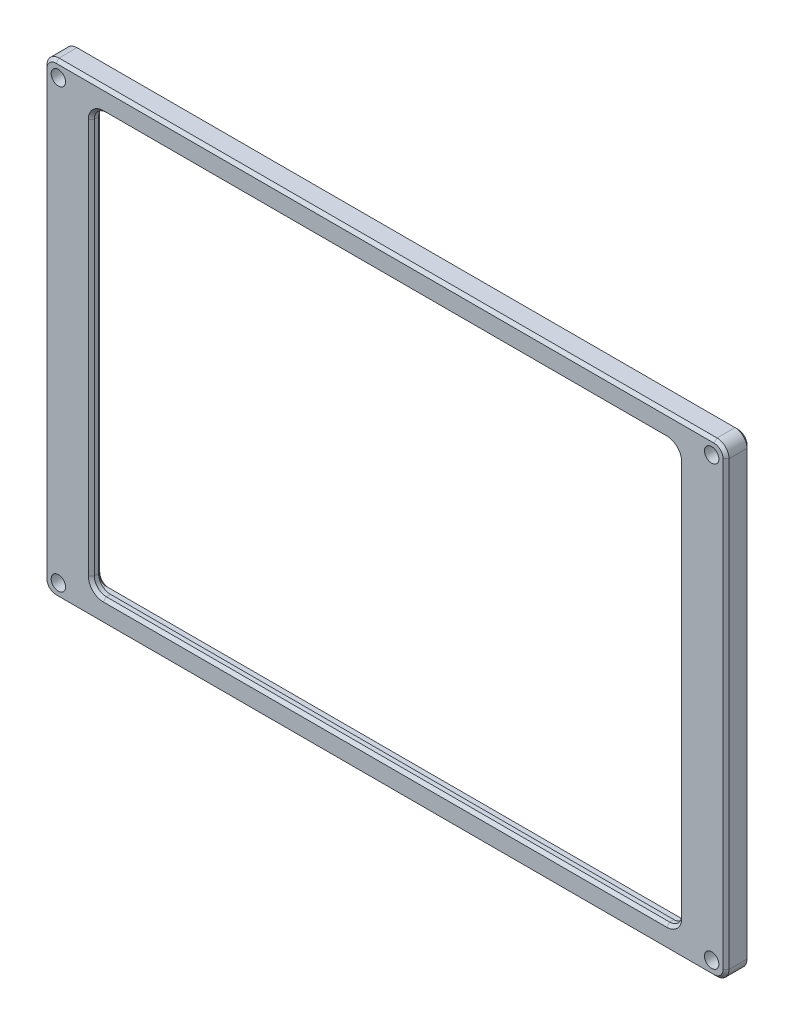
SolidWorks part; units mm, degrees
ref_plane "Front Plane" through (0, 0, 0) normal (0, 0, 1) x (1, 0, 0)
ref_plane "Top Plane" through (0, 0, 0) normal (0, 1, 0) x (1, 0, 0)
ref_plane "Right Plane" through (0, 0, 0) normal (1, 0, 0) x (0, 0, -1)
sketch "Sketch1" plane through (0, 0, 0) normal (0, 0, 1) x (1, 0, 0)
  line L1 (-56.9, -38.9) -> (56.9, -38.9)
  line L2 (-56.9, -38.9) -> (-56.9, 38.9)
  line L3 (-56.9, 38.9) -> (56.9, 38.9)
  line L4 (56.9, -38.9) -> (56.9, 38.9)
  line L5 (-56.9, -38.9) -> (56.9, 38.9) construction
  line L6 (-56.9, 38.9) -> (56.9, -38.9) construction
  line L7 (-49, -35) -> (49, -35)
  line L8 (-49, -35) -> (-49, 35)
  line L9 (-49, 35) -> (49, 35)
  line L10 (49, -35) -> (49, 35)
  line L11 (-49, -35) -> (49, 35) construction
  line L12 (-49, 35) -> (49, -35) construction
  point P0 (0, 0)
  point P5 (0, 0)
  dimension "D1" = 113.8
  dimension "D2" = 77.8
  dimension "D3" = 70
  dimension "D4" = 98
extrude "Boss-Extrude1" add sketch "Sketch1" along normal blind 4
hole_wizard "M2 Clearance Hole1" positions "Sketch2" profile "Sketch3" hole size "M2" standard "ANSI Metric" end condition up to next
sketch "Sketch2" plane through (0, 0, 4) normal (0, 0, 1) x (1, 0, 0)
  line L1 (-54.5, -36.5) -> (54.5, -36.5)
  line L2 (-54.5, -36.5) -> (-54.5, 36.5)
  line L3 (-54.5, 36.5) -> (54.5, 36.5)
  line L4 (54.5, -36.5) -> (54.5, 36.5)
  line L5 (-54.5, -36.5) -> (54.5, 36.5) construction
  line L6 (-54.5, 36.5) -> (54.5, -36.5) construction
  point P1 (0, 0)
  point P2 (54.5, 36.5)
  point P5 (-54.5, -36.5)
  point P6 (-54.5, 36.5)
  point P7 (54.5, -36.5)
  dimension "D1" = 109
  dimension "D2" = 73
sketch "Sketch3" plane through (0, 0, 4) normal (1, 0, 0) x (0, -1, 0)
  line L0 (0, 0) -> (0, 4)
  line L1 (0, 4) -> (1.2, 4)
  line L2 (1.2, 4) -> (1.2, 0)
  line L5 (1.2, 0) -> (0, 0)
  line L11 (0, -6.35) -> (0, 107.95) construction
  dimension "Thru Hole Dia." = 2.4
  dimension "Thru Hole Depth" = 4
fillet "Fillet1" radius 2 4 edges at (56.9, -38.9, 2) (-56.9, -38.9, 2) (56.9, 38.9, 2) (-56.9, 38.9, 2)
fillet "Fillet2" radius 2 4 edges at (49, 35, 2) (-49, -35, 2) (49, -35, 2) (-49, 35, 2)
sketch "Sketch5" plane through (0, 0, 0) normal (0, 0, -1) x (-1, 0, 0)
  line L1 (-51.1, -36.5) -> (51.1, -36.5)
  line L2 (-51.1, -36.5) -> (-51.1, 36.5)
  line L3 (-51.1, 36.5) -> (51.1, 36.5)
  line L4 (51.1, -36.5) -> (51.1, 36.5)
  line L5 (-51.1, -36.5) -> (51.1, 36.5) construction
  line L6 (-51.1, 36.5) -> (51.1, -36.5) construction
  line L16 (-54.9, 38.9) -> (54.9, 38.9) construction
  point P0 (0, 0)
  point P5 (0, 0)
  dimension "D1" = 73
  dimension "D2" = 102.2
  dimension "D4" = 2.4
extrude "Cut-Extrude2" cut sketch "Sketch5" against normal offset from surface (2.8 mm away) 1.2 up to face at (55.7, 36.5, 4)
fillet "Fillet5" radius 1 4 edges at (51.1, -36.5, 1.4) (-51.1, 36.5, 1.4) (-51.1, -36.5, 1.4) (51.1, 36.5, 1.4)
chamfer "Chamfer1" distance 0.5 angle 45 32 edges at (-49, 0, 4) (-48.4142, -34.4142, 4) (-48.4142, 34.4142, 4) (0, -35, 4) (0, 35, 4) (48.4142, -34.4142, 4) (48.4142, 34.4142, 4) (49, 0, 4) (-51.1, 0, 0) (-50.8071, 36.2071, 0) (-50.8071, -36.2071, 0) (0, 36.5, 0) (0, -36.5, 0) (50.8071, 36.2071, 0) (50.8071, -36.2071, 0) (51.1, 0, 0) (0, 38.9, 4) (-56.3142, 38.3142, 4) (56.3142, 38.3142, 4) (-56.9, 0, 4) (56.9, 0, 4) (-56.3142, -38.3142, 4) (56.3142, -38.3142, 4) (0, -38.9, 4) (-56.9, 0, 0) (-56.3142, -38.3142, 0) (-56.3142, 38.3142, 0) (0, -38.9, 0) (0, 38.9, 0) (56.3142, -38.3142, 0) (56.3142, 38.3142, 0) (56.9, 0, 0)
